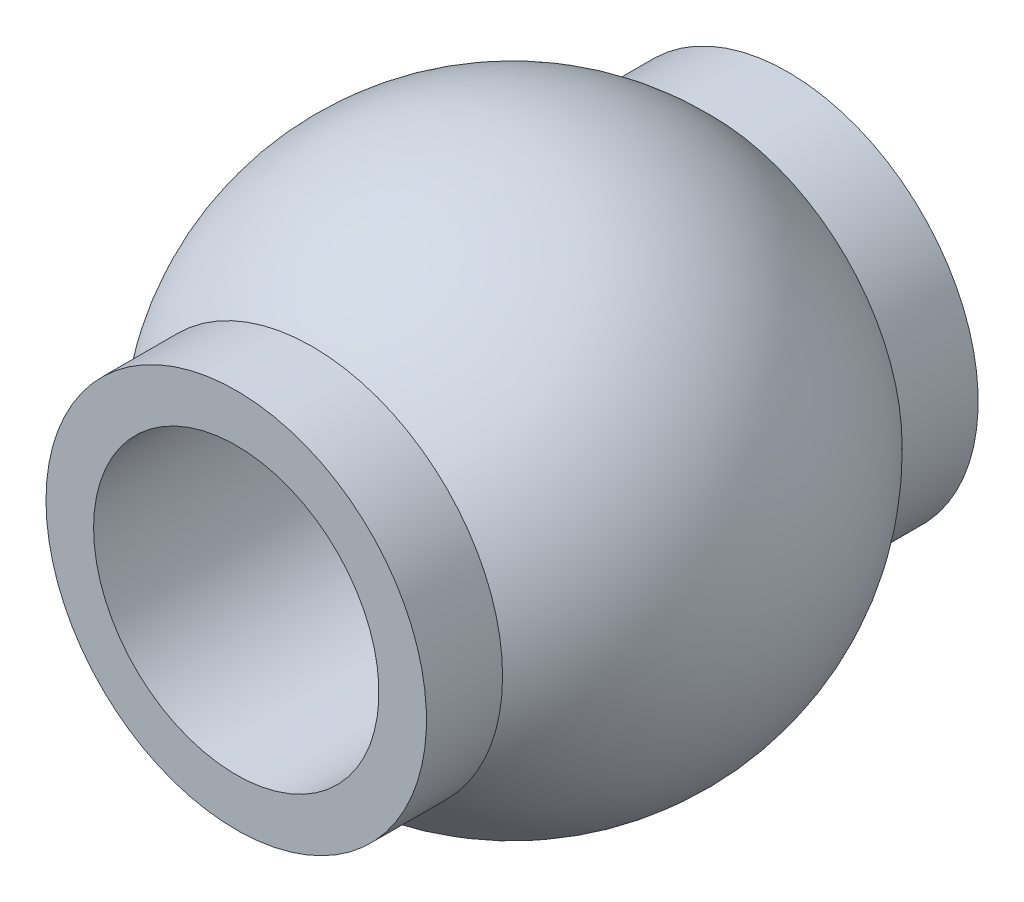
SolidWorks part; units mm, degrees
material "Простая углеродистая сталь"
ref_plane "Спереди" through (0, 0, 0) normal (0, 0, 1) x (1, 0, 0)
ref_plane "Сверху" through (0, 0, 0) normal (0, 1, 0) x (1, 0, 0)
ref_plane "Справа" through (0, 0, 0) normal (1, 0, 0) x (0, 0, -1)
sketch "Эскиз1" plane through (0, 0, 0) normal (0, 1, 0) x (1, 0, 0)
  line L0 (0, 3.557) -> (0, -3.6625) construction
  line L1 (-2, 2.9) -> (0, 2.9)
  line L2 (-2, 2.9) -> (-2, -2.9)
  line L3 (-2, -2.9) -> (2, -2.9)
  line L4 (2, 2.9) -> (2, -2.9)
  line L5 (-2, 2.9) -> (2, -2.9) construction
  line L6 (-2, -2.9) -> (2, 2.9) construction
  line L7 (1.5, 2.9) -> (2, 2.9)
  line L8 (-1.5, 2.9) -> (1.5, 2.9)
  line L9 (-1.5, 2.9) -> (-1.5, -2.9)
  line L10 (-1.5, -2.9) -> (1.5, -2.9)
  line L11 (1.5, 2.9) -> (1.5, -2.9)
  line L12 (-1.5, 2.9) -> (1.5, -2.9) construction
  line L13 (-1.5, -2.9) -> (1.5, 2.9) construction
  circle A0 centre (0, 0) radius 2.9
  dimension "D1" = 4
  dimension "D4" = 3
  dimension "D2" = 5.8
  dimension "D3" = 5.8
revolve "Повернуть1" add sketch "Эскиз1" angle 360 about L0
